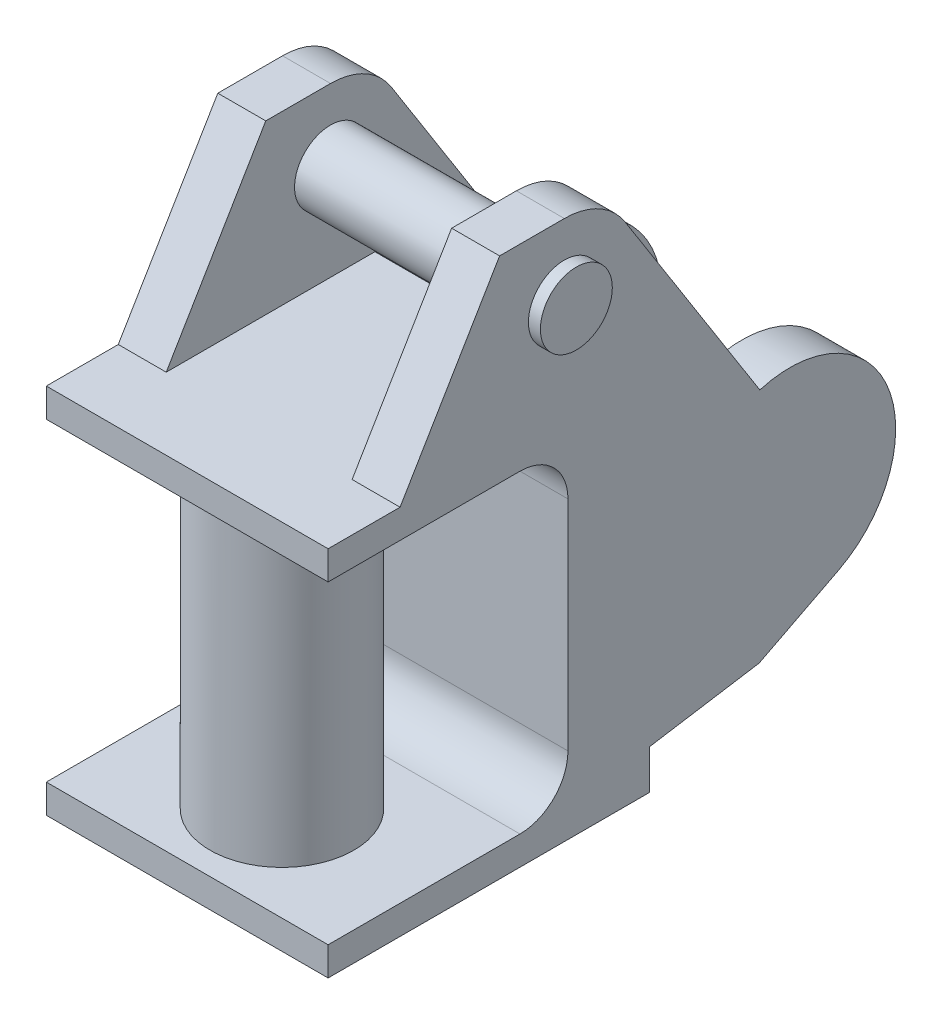
SolidWorks part; units mm, degrees
material "Stainless Steel (ferritic)"
ref_plane "Plano frontal" through (0, 0, 0) normal (0, 0, 1) x (1, 0, 0)
ref_plane "Plano superior" through (0, 0, 0) normal (0, 1, 0) x (1, 0, 0)
ref_plane "Plano direito" through (0, 0, 0) normal (1, 0, 0) x (0, 0, -1)
sketch "Sketch1" plane through (0, 0, 0) normal (1, 0, 0) x (0, 0, -1)
  line L0 (0, 0) -> (268, 0)
  line L1 (268, 0) -> (268, 33)
  line L2 (268, 33) -> (359.3924, 47.676)
  line L3 (359.3924, 47.676) -> (425.2547, 81.4125)
  line L4 (360.0117, 244.6878) -> (247.6944, 422.0949)
  line L5 (197, 450) -> (143, 450)
  line L6 (143, 450) -> (60, 310)
  line L7 (60, 310) -> (0, 310)
  line L8 (0, 310) -> (0, 286)
  line L9 (0, 286) -> (200, 286)
  line L10 (200, 286) -> (200, 24)
  line L11 (200, 24) -> (0, 24)
  line L12 (0, 24) -> (0, 0)
  arc A0 (425.2547, 81.4125) -> (360.0117, 244.6878) centre (385, 160) ccw
  arc A1 (247.6944, 422.0949) -> (197, 450) centre (197, 390) ccw
  circle A2 centre (197, 390) radius 30
  point P20 (230.0275, 450)
  dimension "D6" = 74
  dimension "D10" = 60
  dimension "D5" = 162
  dimension "D17" = 385
  dimension "D18" = 60
  dimension "D1" = 268
  dimension "D2" = 33
  dimension "D3" = 160
  dimension "D4" = 230
  dimension "D7" = 243
  dimension "D8" = 63
  dimension "D9" = 60
  dimension "D11" = 54
  dimension "D12" = 197
  dimension "D13" = 200
  dimension "D14" = 310
  dimension "D15" = 262
  dimension "D16" = 24
extrude "Boss-Extrude1" add sketch "Sketch1" along normal blind 40
ref_plane "Plane1" through (-77.5, 0, 0) normal (1, 0, 0) x (0, 0, -1)
mirror "Mirror3" about plane through (-77.5, 0, 0) normal (1, 0, 0) of bodies 101
sketch "Sketch2" plane through (-77.5, 0, 0) normal (1, 0, 0) x (0, 0, -1)
  line L0 (0, 0) -> (234, 0)
  line L1 (0, 0) -> (268, 0) construction
  line L2 (234, 0) -> (234, 310)
  line L3 (234, 310) -> (0, 310)
  line L4 (0, 310) -> (0, 286)
  line L5 (0, 286) -> (200, 286)
  line L6 (200, 286) -> (200, 24)
  line L7 (200, 24) -> (0, 24)
  line L8 (0, 24) -> (0, 0)
  dimension "D1" = 234
extrude "Boss-Extrude2" add sketch "Sketch2" along normal mid plane 155
fillet "Fillet1" radius 40 2 edges at (-77.5, 286, -200) (-77.5, 24, -200)
sketch "Sketch3" plane through (-77.5, 0, 0) normal (1, 0, 0) x (0, 0, -1)
  circle A0 centre (197, 390) radius 30
extrude "Boss-Extrude3" add sketch "Sketch3" along normal mid plane 255
sketch "Sketch4" plane through (-77.5, 0, 0) normal (1, 0, 0) x (0, 0, -1)
  circle A0 centre (385, 160) radius 20
  dimension "D1" = 40
extrude "Boss-Extrude4" add sketch "Sketch4" along normal mid plane 155 separate body
sketch "Sketch5" plane through (0, 0, 0) normal (0, 1, 0) x (1, 0, 0)
  line L0 (40, 0) -> (-195, 0) construction
  circle A0 centre (-77.5, 79) radius 60
  point P5 (-77.5, 0)
  dimension "D1" = 120
  dimension "D2" = 79
extrude "Boss-Extrude5" add sketch "Sketch5" along normal up to surface (286 mm away) up to face at (-77.5, 286, -80)
